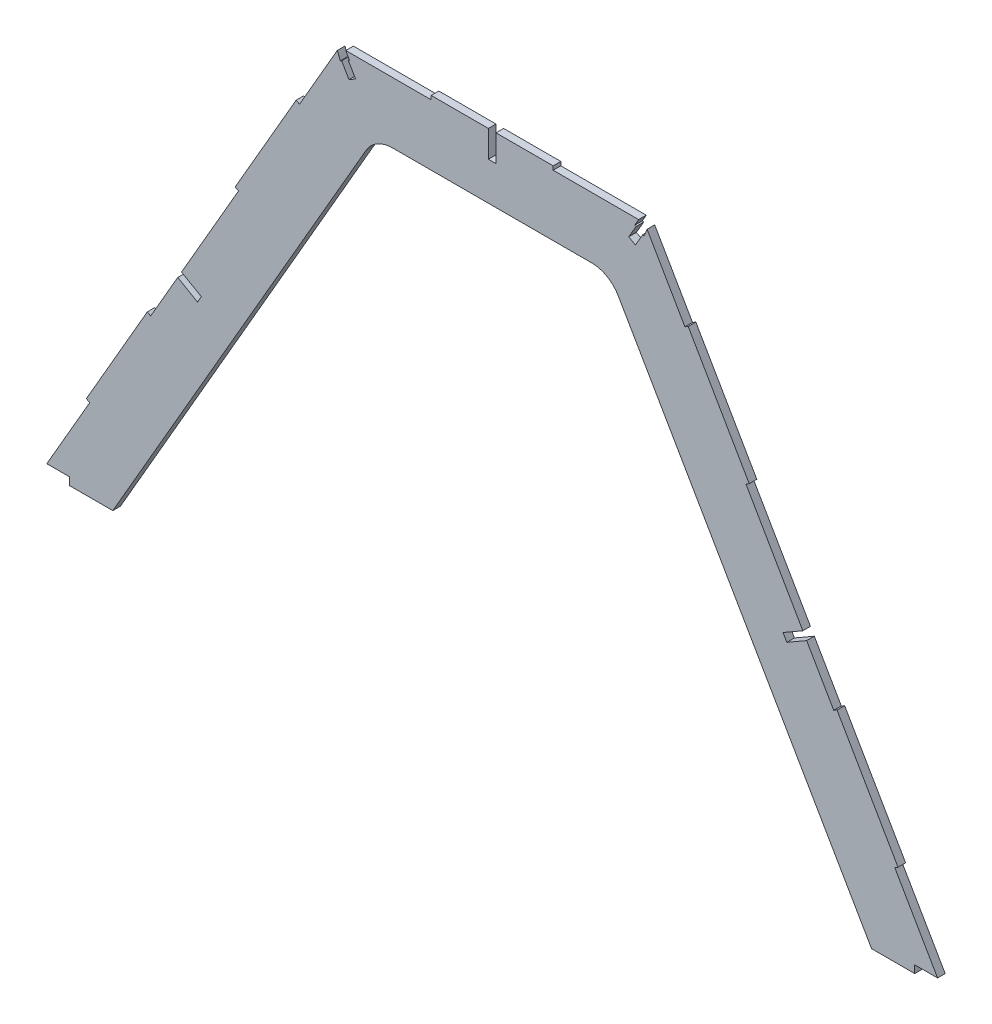
SolidWorks part; units mm, degrees
material "Balsa"
ref_plane "Front Plane" through (0, 0, 0) normal (0, 0, 1) x (1, 0, 0)
ref_plane "Top Plane" through (0, 0, 0) normal (0, 1, 0) x (1, 0, 0)
ref_plane "Right Plane" through (0, 0, 0) normal (1, 0, 0) x (0, 0, -1)
sketch "Sketch1" plane through (0, 0, 0) normal (0, 0, 1) x (1, 0, 0)
  line L0 (-196.85, 0) -> (-63.5, 230.969)
  line L1 (-63.5, 230.969) -> (63.5, 230.969)
  line L2 (63.5, 230.969) -> (196.85, 0)
  line L9 (-167.5206, 0) -> (-48.8353, 205.569)
  line L10 (-48.8353, 205.569) -> (48.8353, 205.569)
  line L11 (48.8353, 205.569) -> (167.5206, 0)
  line L12 (-196.85, 0) -> (-167.5206, 0)
  line L13 (196.85, 0) -> (167.5206, 0)
  line L14 (-174.853, -12.7) -> (-48.8353, 205.569) construction
  line L15 (48.8353, 205.569) -> (174.853, -12.7) construction
  point P14 (0, 205.569)
  dimension "D1" = 127
  dimension "D2" = 120
  dimension "D3" = 25.4
  dimension "D4" = 266.7
  dimension "D5" = 266.7
extrude "Boss-Extrude1" add sketch "Sketch1" along normal blind 3.175
fillet "Fillet1" radius 12.7 4 edges at (167.5206, 0, 1.5875) (-167.5206, 0, 1.5875) (48.8353, 205.569, 1.5875) (-48.8353, 205.569, 1.5875)
sketch "Sketch3" plane through (0, 0, 0) normal (0, 0, -1) x (-1, 0, 0)
  line L0 (80.264, 201.9329) -> (81.6388, 202.7266)
  line L1 (81.6388, 202.7266) -> (107.0388, 158.7325)
  line L2 (107.0388, 158.7325) -> (105.664, 157.9388)
  line L3 (142.24, 94.5873) -> (143.6148, 95.381)
  line L4 (143.6148, 95.381) -> (169.0148, 51.387)
  line L5 (169.0148, 51.387) -> (167.64, 50.5932)
  line L6 (0, 230.969) -> (0, 176.3712) construction
  line L7 (63.5, 230.969) -> (196.85, 0) construction
  line L8 (25.4, 230.969) -> (-25.4, 230.969)
  line L9 (25.4, 230.969) -> (25.4, 232.5565)
  line L10 (25.4, 232.5565) -> (-25.4, 232.5565)
  line L11 (-25.4, 230.969) -> (-25.4, 232.5565)
  line L12 (80.264, 201.9329) -> (105.664, 157.9388)
  line L13 (167.64, 50.5932) -> (142.24, 94.5873)
  line L16 (-196.85, 0) -> (-174.853, 0)
  line L17 (-163.8544, 6.35) -> (-52.5015, 199.219)
  line L18 (-41.503, 205.569) -> (41.503, 205.569)
  line L19 (52.5015, 199.219) -> (163.8544, 6.35)
  line L20 (174.853, 0) -> (196.85, 0)
  line L21 (196.85, 0) -> (63.5, 230.969)
  line L22 (63.5, 230.969) -> (-63.5, 230.969)
  line L30 (25.4, 230.969) -> (-25.4, 230.969)
  line L42 (-63.5, 230.969) -> (-196.85, 0)
  arc A8 (-174.853, 0) -> (-163.8544, 6.35) centre (-174.853, 12.7) ccw
  arc A9 (-41.503, 205.569) -> (-52.5015, 199.219) centre (-41.503, 192.869) ccw
  arc A10 (52.5015, 199.219) -> (41.503, 205.569) centre (41.503, 192.869) ccw
  arc A11 (163.8544, 6.35) -> (174.853, 0) centre (174.853, 12.7) ccw
  point P30 (0, 230.969)
  dimension "D2" = 1.5875
  dimension "D3" = 33.528
  dimension "D4" = 73.152
  dimension "D5" = 50.8
  dimension "D6" = 50.8
  dimension "D7" = 50.8
  dimension "D8" = 1.5875
  dimension "D1" = 0
extrude "Boss-Extrude2" add sketch "Sketch3" against normal up to surface (3.175 mm away) up to face at (0, 107.0178, 3.175)
sketch "Sketch4" plane through (0, 0, 0) normal (0, 0, -1) x (-1, 0, 0)
  line L0 (-63.5, 230.969) -> (-47.853, 203.8675) construction
  line L1 (-61.6669, 230.969) -> (-56.9044, 222.7201)
  line L2 (-63.5, 230.969) -> (-25.4, 230.969) construction
  line L3 (-61.6669, 230.969) -> (-63.5, 230.969)
  line L4 (-64.4165, 229.3815) -> (-63.5, 230.969)
  line L5 (-64.4165, 229.3815) -> (-59.654, 221.1326)
  line L6 (-56.9044, 222.7201) -> (-59.654, 221.1326)
  arc A0 (-41.503, 205.569) -> (-52.5015, 199.219) centre (-41.503, 192.869) ccw construction
  dimension "D1" = 9.525
  dimension "D2" = 1.5875
sketch "Sketch5" plane through (0, 0, 0) normal (0, 0, -1) x (-1, 0, 0)
  line L0 (-130.175, 115.4845) -> (-240.9783, 179.4568) construction
  line L1 (-196.85, 0) -> (-63.5, 230.969) construction
  line L2 (-129.3812, 116.8593) -> (-121.1324, 112.0968)
  line L3 (-130.9688, 114.1097) -> (-122.7199, 109.3472)
  line L4 (-121.1324, 112.0968) -> (-122.7199, 109.3472)
  line L5 (-129.3812, 116.8593) -> (-130.9688, 114.1097)
  line L7 (-175.9669, 19.6728) -> (-185.4919, 19.6728)
  line L11 (-185.4919, 19.6728) -> (-187.325, 16.4978)
  line L12 (-175.9669, 19.6728) -> (-175.9669, 16.4978)
  line L13 (-175.9669, 16.4978) -> (-187.325, 16.4978)
  line L14 (-186.309, 16.4978) -> (-195.834, 0)
  line L15 (-174.853, 0) -> (-196.85, 0) construction
  line L16 (-195.834, 0) -> (-196.85, 0)
  line L17 (-187.325, 16.4978) -> (-196.85, 0)
  line L18 (-187.325, 16.4978) -> (-186.309, 16.4978)
  line M5 (-196.85, 0) -> (-174.853, 0)
  line M16 (-63.5, 230.969) -> (-196.85, 0)
  dimension "D1" = 1.5875
  dimension "D2" = 9.525
  dimension "D3" = 19.05
  dimension "D4" = 9.525
  dimension "D5" = 1.016
  dimension "D6" = 3.175
  dimension "D7" = 1.016
extrude "Cut-Extrude1" cut sketch "Sketch5" against normal through all contours L13 L12 L7 M16 | L14 L13 M16 M5 | L4 L2 L5 L3 M16
extrude "Cut-Extrude2" cut sketch "Sketch4" against normal through all
mirror "Mirror1" about plane through (0, 0, 0) normal (1, 0, 0) of "Boss-Extrude2", "Cut-Extrude1", "Cut-Extrude2"
sketch "Sketch6" plane through (0, 0, 0) normal (0, 0, -1) x (-1, 0, 0)
  line L0 (0, 232.5565) -> (0, 225.5658) construction
  line L2 (-1.5875, 221.444) -> (1.5875, 221.444)
  line L3 (1.5875, 221.444) -> (1.5875, 232.5565)
  line L4 (25.4, 232.5565) -> (-25.4, 232.5565) construction
  line L5 (1.5875, 232.5565) -> (-1.5875, 232.5565)
  line L6 (-1.5875, 232.5565) -> (-1.5875, 221.444)
  point P6 (0, 221.444)
  dimension "D1" = 3.175
  dimension "D2" = 11.1125
extrude "Cut-Extrude3" cut sketch "Sketch6" against normal up to next contours L6 L2 L3 L5
sketch "Sketch7" plane through (0, 0, 0) normal (0, 0, -1) x (-1, 0, 0)
  line L0 (-64.4986, 229.2394) -> (-63.2478, 226.1102)
  line L1 (-80.264, 201.9329) -> (-64.4165, 229.3815) construction
  line L2 (-63.2478, 226.1102) -> (-59.4008, 228.1785)
  line L3 (-59.4008, 228.1785) -> (-60.98, 230.969)
  line L4 (-61.6669, 230.969) -> (-25.4, 230.969) construction
  line L5 (-64.4986, 229.2394) -> (-64.4165, 229.3815)
  line L6 (-64.4165, 229.3815) -> (-59.654, 221.1326)
  line L7 (-59.654, 221.1326) -> (-56.9044, 222.7201)
  line L9 (-61.6669, 230.969) -> (-60.98, 230.969)
  line L11 (-61.6669, 230.969) -> (-64.4165, 229.3815)
  line L12 (0, 1.7463) -> (0, -1.7463) construction
  line L13 (61.6669, 230.969) -> (64.4165, 229.3815)
  line L14 (61.6669, 230.969) -> (60.98, 230.969)
  line L15 (64.4986, 229.2394) -> (64.4165, 229.3815)
  line L16 (59.4008, 228.1785) -> (60.98, 230.969)
  line L17 (63.2478, 226.1102) -> (59.4008, 228.1785)
  line L18 (64.4986, 229.2394) -> (63.2478, 226.1102)
  dimension "D1" = 128.212
  dimension "D2" = 3.3699
  dimension "D3" = 0.1641
  dimension "D4" = 83.523
  dimension "D5" = 0.6869
  dimension "D6" = 2.7905
extrude "Cut-Extrude5" cut sketch "Sketch7" against normal up to next contours L9 L11 L6 L2 L3 | L6 L5 L0 L2 | L18 L15 L13 L14 L16 L17
sketch "Sketch8" plane through (0, 0, 0) normal (0, 0, -1) x (-1, 0, 0)
  line L1 (-246.8797, 16.4978) -> (224.1225, 16.4978)
  line L2 (-246.8797, 16.4978) -> (-246.8797, -6.1758)
  line L3 (-246.8797, -6.1758) -> (224.1225, -6.1758)
  line L4 (224.1225, 16.4978) -> (224.1225, -6.1758)
extrude "Cut-Extrude6" cut sketch "Sketch8" against normal through all
